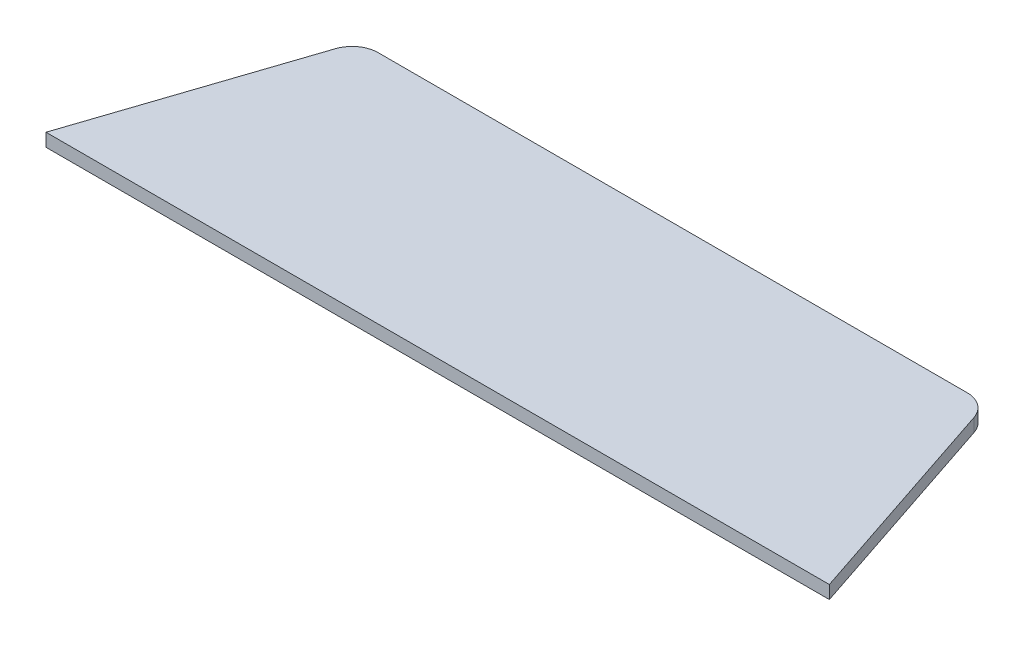
SolidWorks part; units mm, degrees
ref_plane "Front Plane" through (0, 0, 0) normal (0, 0, 1) x (1, 0, 0)
ref_plane "Top Plane" through (0, 0, 0) normal (0, 1, 0) x (1, 0, 0)
ref_plane "Right Plane" through (0, 0, 0) normal (1, 0, 0) x (0, 0, -1)
sketch "Sketch1" plane through (0, 0, 0) normal (0, 1, 0) x (1, 0, 0)
  line L0 (0, 0) -> (30, 90)
  line L1 (0, 0) -> (300, 0)
  line L3 (30, 90) -> (270, 90)
  line L5 (300, 0) -> (270, 90)
  dimension "D1" = 90
  dimension "D2" = 240
  dimension "D3" = 300
extrude "Boss-Extrude1" add sketch "Sketch1" along normal blind 5
fillet "Fillet1" radius 10 2 edges at (270, 2.5, -90) (30, 2.5, -90)
